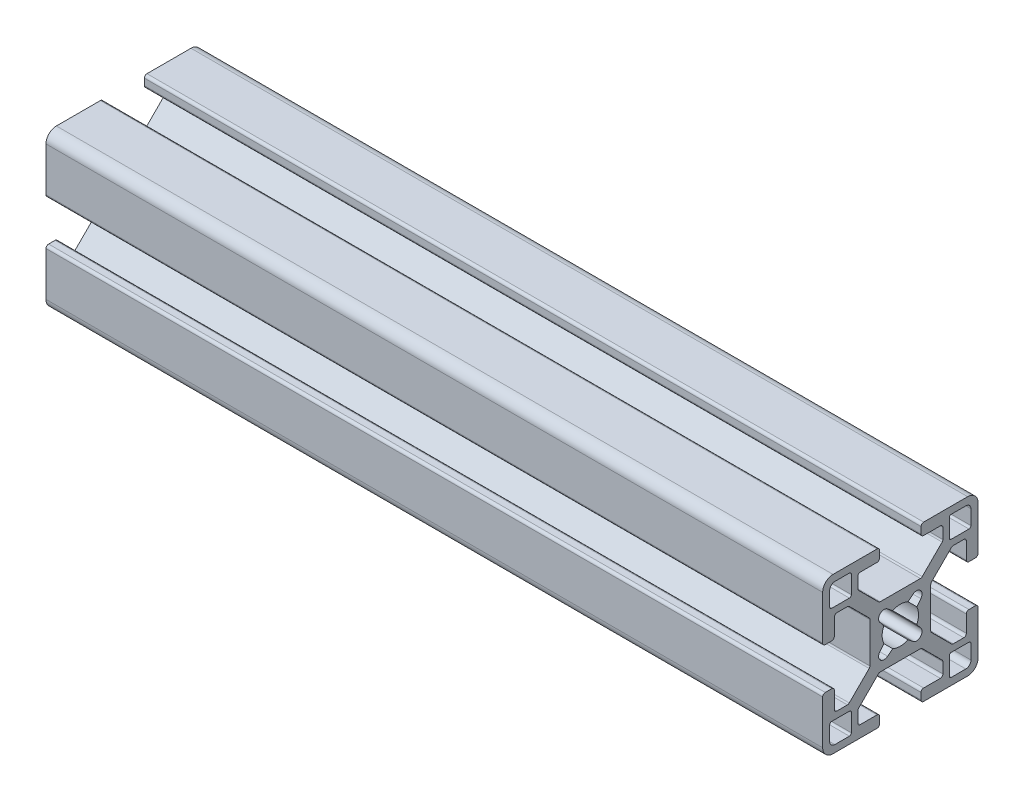
SolidWorks part; units mm, degrees
ref_plane "Front" through (0, 0, 0) normal (0, 0, 1) x (1, 0, 0)
ref_plane "Top" through (0, 0, 0) normal (0, 1, 0) x (1, 0, 0)
ref_plane "Right" through (0, 0, 0) normal (1, 0, 0) x (0, 0, -1)
sketch3d "3DSketch1"
  line L0 (0, 0, 0) -> (150, 0, 0)
  dimension "D1" = 150
other "Perfil com. aluminio PERFIL COMER. 30 X 30(1)"
ref_plane "Plano1" through (0, 0, 0) normal (1, 0, 0) x (0, 0, -1)
sketch "Esboço1" plane through (0, 0, 0) normal (1, 0, 0) x (0, 0, -1)
  line L10 (-3.1849, 1.488) -> (-3.9634, 2.4631)
  line L11 (-2.4631, 3.9634) -> (-1.488, 3.1849)
  line L16 (-9.46, 13.26) -> (-9.46, 9.84)
  line L17 (-9.84, 9.46) -> (-13.26, 9.46)
  line L18 (-13.64, 9.84) -> (-13.64, 12.64)
  line L19 (-12.64, 13.64) -> (-9.84, 13.64)
  line L44 (0, 5.8727) -> (-3.8729, 5.8727)
  line L45 (-4.2264, 6.0192) -> (-8.0736, 9.8663)
  line L46 (-8.22, 10.2198) -> (-8.22, 12.25)
  line L47 (-7.72, 12.75) -> (-4.5, 12.75)
  line L48 (-4, 13.25) -> (-4, 14.5)
  line L49 (-4.5, 15) -> (-13, 15)
  line L50 (-15, 13) -> (-15, 4.5)
  line L51 (-14.5, 4) -> (-13.25, 4)
  line L52 (-12.75, 4.5) -> (-12.75, 7.72)
  line L53 (-12.25, 8.22) -> (-10.2198, 8.22)
  line L54 (-9.8663, 8.0736) -> (-6.0192, 4.2264)
  line L55 (-5.8727, 3.8729) -> (-5.8727, 0)
  line L84 (13.64, 12.64) -> (13.64, 9.84)
  line L91 (15, 4.5) -> (15, 13)
  line L92 (13, 15) -> (4.5, 15)
  line L93 (4, 14.5) -> (4, 13.25)
  line L94 (4.5, 12.75) -> (7.72, 12.75)
  line L95 (8.22, 12.25) -> (8.22, 10.2198)
  line L96 (8.0736, 9.8663) -> (4.2264, 6.0192)
  line L97 (3.8729, 5.8727) -> (0, 5.8727)
  line L98 (1.488, 3.1849) -> (2.4631, 3.9634)
  line L99 (3.9634, 2.4631) -> (3.1849, 1.488)
  line L100 (5.8727, 0) -> (5.8727, 3.8729)
  line L101 (6.0192, 4.2264) -> (9.8663, 8.0736)
  line L102 (10.2198, 8.22) -> (12.25, 8.22)
  line L103 (12.75, 7.72) -> (12.75, 4.5)
  line L104 (13.25, 4) -> (14.5, 4)
  line L105 (13.26, 9.46) -> (9.84, 9.46)
  line L112 (9.46, 9.84) -> (9.46, 13.26)
  line L113 (9.84, 13.64) -> (12.64, 13.64)
  line L114 (12.64, -13.64) -> (9.84, -13.64)
  line L115 (4.5, -15) -> (13, -15)
  line L116 (15, -13) -> (15, -4.5)
  line L117 (14.5, -4) -> (13.25, -4)
  line L118 (12.75, -4.5) -> (12.75, -7.72)
  line L119 (12.25, -8.22) -> (10.2198, -8.22)
  line L120 (9.8663, -8.0736) -> (6.0192, -4.2264)
  line L121 (5.8727, -3.8729) -> (5.8727, 0)
  line L122 (3.1849, -1.488) -> (3.9634, -2.4631)
  line L123 (2.4631, -3.9634) -> (1.488, -3.1849)
  line L124 (0, -5.8727) -> (3.8729, -5.8727)
  line L125 (4.2264, -6.0192) -> (8.0736, -9.8663)
  line L126 (8.22, -10.2198) -> (8.22, -12.25)
  line L133 (7.72, -12.75) -> (4.5, -12.75)
  line L134 (4, -13.25) -> (4, -14.5)
  line L135 (9.46, -13.26) -> (9.46, -9.84)
  line L136 (9.84, -9.46) -> (13.26, -9.46)
  line L137 (13.64, -9.84) -> (13.64, -12.64)
  line L138 (-13.64, -12.64) -> (-13.64, -9.84)
  line L139 (-15, -4.5) -> (-15, -13)
  line L140 (-13, -15) -> (-4.5, -15)
  line L141 (-4, -14.5) -> (-4, -13.25)
  line L142 (-4.5, -12.75) -> (-7.72, -12.75)
  line L143 (-8.22, -12.25) -> (-8.22, -10.2198)
  line L144 (-8.0736, -9.8663) -> (-4.2264, -6.0192)
  line L145 (-3.8729, -5.8727) -> (0, -5.8727)
  line L146 (-1.488, -3.1849) -> (-2.4631, -3.9634)
  line L147 (-3.9634, -2.4631) -> (-3.1849, -1.488)
  line L148 (3.9634, 2.4631) -> (3.1849, 1.488) [skipped]
  line L149 (13.26, 9.46) -> (9.84, 9.46) [skipped]
  line L150 (9.46, 9.84) -> (9.46, 13.26) [skipped]
  line L151 (9.84, 13.64) -> (12.64, 13.64) [skipped]
  line L152 (13.64, 12.64) -> (13.64, 9.84) [skipped]
  line L153 (5.8727, 0) -> (5.8727, 3.8729) [skipped]
  line L154 (6.0192, 4.2264) -> (9.8663, 8.0736) [skipped]
  line L155 (10.2198, 8.22) -> (12.25, 8.22) [skipped]
  line L156 (12.75, 7.72) -> (12.75, 4.5) [skipped]
  line L157 (13.25, 4) -> (14.5, 4) [skipped]
  line L158 (15, 4.5) -> (15, 13) [skipped]
  line L159 (13, 15) -> (4.5, 15) [skipped]
  line L160 (4, 14.5) -> (4, 13.25) [skipped]
  line L161 (4.5, 12.75) -> (7.72, 12.75) [skipped]
  line L162 (8.22, 12.25) -> (8.22, 10.2198) [skipped]
  line L163 (8.0736, 9.8663) -> (4.2264, 6.0192) [skipped]
  line L164 (3.8729, 5.8727) -> (0, 5.8727) [skipped]
  line L165 (3.1849, -1.488) -> (3.9634, -2.4631) [skipped]
  line L166 (9.46, -13.26) -> (9.46, -9.84) [skipped]
  line L167 (9.84, -9.46) -> (13.26, -9.46) [skipped]
  line L168 (13.64, -9.84) -> (13.64, -12.64) [skipped]
  line L169 (12.64, -13.64) -> (9.84, -13.64) [skipped]
  line L170 (0, -5.8727) -> (3.8729, -5.8727) [skipped]
  line L171 (4.2264, -6.0192) -> (8.0736, -9.8663) [skipped]
  line L172 (8.22, -10.2198) -> (8.22, -12.25) [skipped]
  line L173 (7.72, -12.75) -> (4.5, -12.75) [skipped]
  line L174 (4, -13.25) -> (4, -14.5) [skipped]
  line L175 (4.5, -15) -> (13, -15) [skipped]
  line L176 (15, -13) -> (15, -4.5) [skipped]
  line L177 (14.5, -4) -> (13.25, -4) [skipped]
  line L178 (12.75, -4.5) -> (12.75, -7.72) [skipped]
  line L179 (12.25, -8.22) -> (10.2198, -8.22) [skipped]
  line L180 (9.8663, -8.0736) -> (6.0192, -4.2264) [skipped]
  line L181 (5.8727, -3.8729) -> (5.8727, 0) [skipped]
  line L182 (-9.46, -9.84) -> (-9.46, -13.26) [skipped]
  line L183 (-9.84, -13.64) -> (-12.64, -13.64) [skipped]
  line L184 (-13.64, -12.64) -> (-13.64, -9.84) [skipped]
  line L185 (-15, -4.5) -> (-15, -13) [skipped]
  line L186 (-13, -15) -> (-4.5, -15) [skipped]
  line L187 (-4, -14.5) -> (-4, -13.25) [skipped]
  line L188 (-4.5, -12.75) -> (-7.72, -12.75) [skipped]
  line L189 (-8.22, -12.25) -> (-8.22, -10.2198) [skipped]
  line L190 (2.4631, -3.9634) -> (1.488, -3.1849) [skipped]
  line L191 (-1.488, -3.1849) -> (-2.4631, -3.9634) [skipped]
  line L192 (-13.26, -9.46) -> (-9.84, -9.46) [skipped]
  line L193 (-6.0192, -4.2264) -> (-9.8663, -8.0736) [skipped]
  line L194 (-10.2198, -8.22) -> (-12.25, -8.22) [skipped]
  line L195 (-12.75, -7.72) -> (-12.75, -4.5) [skipped]
  line L196 (-13.25, -4) -> (-14.5, -4) [skipped]
  line L197 (-8.0736, -9.8663) -> (-4.2264, -6.0192) [skipped]
  line L198 (-3.8729, -5.8727) -> (0, -5.8727) [skipped]
  line L199 (1.488, 3.1849) -> (2.4631, 3.9634) [skipped]
  line L200 (-3.9634, -2.4631) -> (-3.1849, -1.488) [skipped]
  line L201 (-5.8727, 0) -> (-5.8727, -3.8729) [skipped]
  line L202 (-5.8727, 0) -> (-5.8727, -3.8729)
  line L203 (-6.0192, -4.2264) -> (-9.8663, -8.0736)
  line L204 (-10.2198, -8.22) -> (-12.25, -8.22)
  line L205 (-12.75, -7.72) -> (-12.75, -4.5)
  line L206 (-13.25, -4) -> (-14.5, -4)
  line L207 (-13.26, -9.46) -> (-9.84, -9.46)
  line L208 (-9.46, -9.84) -> (-9.46, -13.26)
  line L209 (-9.84, -13.64) -> (-12.64, -13.64)
  arc A10 (-3.1849, 1.488) -> (-3.5154, 0) centre (0, 0) ccw
  arc A11 (-2.4631, 3.9634) -> (-3.9634, 2.4631) centre (-3.1292, 3.1292) ccw
  arc A12 (0, 3.5154) -> (-1.488, 3.1849) centre (0, 0) ccw
  arc A16 (-9.46, 13.26) -> (-9.84, 13.64) centre (-9.84, 13.26) ccw
  arc A17 (-9.84, 9.46) -> (-9.46, 9.84) centre (-9.84, 9.84) ccw
  arc A18 (-13.64, 9.84) -> (-13.26, 9.46) centre (-13.26, 9.84) ccw
  arc A19 (-12.64, 13.64) -> (-13.64, 12.64) centre (-12.64, 12.64) ccw
  arc A41 (-7.72, 12.75) -> (-8.22, 12.25) centre (-7.72, 12.25) ccw
  arc A42 (-4.5, 12.75) -> (-4, 13.25) centre (-4.5, 13.25) ccw
  arc A43 (-4, 14.5) -> (-4.5, 15) centre (-4.5, 14.5) ccw
  arc A44 (-13, 15) -> (-15, 13) centre (-13, 13) ccw
  arc A45 (-15, 4.5) -> (-14.5, 4) centre (-14.5, 4.5) ccw
  arc A46 (-13.25, 4) -> (-12.75, 4.5) centre (-13.25, 4.5) ccw
  arc A47 (-12.25, 8.22) -> (-12.75, 7.72) centre (-12.25, 7.72) ccw
  arc A50 (-6.0192, 4.2264) -> (-5.8727, 3.8729) centre (-6.3727, 3.8729) cw
  arc A51 (-4.2264, 6.0192) -> (-3.8729, 5.8727) centre (-3.8729, 6.3727) ccw
  arc A52 (-8.22, 10.2198) -> (-8.0736, 9.8663) centre (-7.72, 10.2198) ccw
  arc A53 (-10.2198, 8.22) -> (-9.8663, 8.0736) centre (-10.2198, 7.72) cw
  arc A68 (15, 13) -> (13, 15) centre (13, 13) ccw
  arc A69 (13.64, 12.64) -> (12.64, 13.64) centre (12.64, 12.64) ccw
  arc A70 (4.5, 15) -> (4, 14.5) centre (4.5, 14.5) ccw
  arc A71 (4, 13.25) -> (4.5, 12.75) centre (4.5, 13.25) ccw
  arc A79 (8.22, 12.25) -> (7.72, 12.75) centre (7.72, 12.25) ccw
  arc A80 (8.22, 10.2198) -> (8.0736, 9.8663) centre (7.72, 10.2198) cw
  arc A81 (4.2264, 6.0192) -> (3.8729, 5.8727) centre (3.8729, 6.3727) cw
  arc A82 (1.488, 3.1849) -> (0, 3.5154) centre (0, 0) ccw
  arc A83 (3.9634, 2.4631) -> (2.4631, 3.9634) centre (3.1292, 3.1292) ccw
  arc A84 (3.5154, 0) -> (3.1849, 1.488) centre (0, 0) ccw
  arc A85 (6.0192, 4.2264) -> (5.8727, 3.8729) centre (6.3727, 3.8729) ccw
  arc A86 (10.2198, 8.22) -> (9.8663, 8.0736) centre (10.2198, 7.72) ccw
  arc A87 (12.75, 7.72) -> (12.25, 8.22) centre (12.25, 7.72) ccw
  arc A88 (12.75, 4.5) -> (13.25, 4) centre (13.25, 4.5) ccw
  arc A89 (14.5, 4) -> (15, 4.5) centre (14.5, 4.5) ccw
  arc A97 (13.26, 9.46) -> (13.64, 9.84) centre (13.26, 9.84) ccw
  arc A98 (9.46, 9.84) -> (9.84, 9.46) centre (9.84, 9.84) ccw
  arc A99 (9.84, 13.64) -> (9.46, 13.26) centre (9.84, 13.26) ccw
  arc A100 (13, -15) -> (15, -13) centre (13, -13) ccw
  arc A101 (12.64, -13.64) -> (13.64, -12.64) centre (12.64, -12.64) ccw
  arc A102 (15, -4.5) -> (14.5, -4) centre (14.5, -4.5) ccw
  arc A103 (13.25, -4) -> (12.75, -4.5) centre (13.25, -4.5) ccw
  arc A104 (12.25, -8.22) -> (12.75, -7.72) centre (12.25, -7.72) ccw
  arc A105 (10.2198, -8.22) -> (9.8663, -8.0736) centre (10.2198, -7.72) cw
  arc A106 (6.0192, -4.2264) -> (5.8727, -3.8729) centre (6.3727, -3.8729) cw
  arc A107 (3.1849, -1.488) -> (3.5154, 0) centre (0, 0) ccw
  arc A108 (3.9634, 2.4631) -> (2.4631, 3.9634) centre (3.1292, 3.1292) ccw [skipped]
  arc A109 (13.26, 9.46) -> (13.64, 9.84) centre (13.26, 9.84) ccw [skipped]
  arc A110 (9.46, 9.84) -> (9.84, 9.46) centre (9.84, 9.84) ccw [skipped]
  arc A111 (9.84, 13.64) -> (9.46, 13.26) centre (9.84, 13.26) ccw [skipped]
  arc A112 (13.64, 12.64) -> (12.64, 13.64) centre (12.64, 12.64) ccw [skipped]
  arc A113 (12.75, 7.72) -> (12.25, 8.22) centre (12.25, 7.72) ccw [skipped]
  arc A114 (12.75, 4.5) -> (13.25, 4) centre (13.25, 4.5) ccw [skipped]
  arc A115 (14.5, 4) -> (15, 4.5) centre (14.5, 4.5) ccw [skipped]
  arc A116 (15, 13) -> (13, 15) centre (13, 13) ccw [skipped]
  arc A117 (4.5, 15) -> (4, 14.5) centre (4.5, 14.5) ccw [skipped]
  arc A118 (4, 13.25) -> (4.5, 12.75) centre (4.5, 13.25) ccw [skipped]
  arc A119 (8.22, 12.25) -> (7.72, 12.75) centre (7.72, 12.25) ccw [skipped]
  arc A120 (4.2264, 6.0192) -> (3.8729, 5.8727) centre (3.8729, 6.3727) cw [skipped]
  arc A121 (6.0192, 4.2264) -> (5.8727, 3.8729) centre (6.3727, 3.8729) ccw [skipped]
  arc A122 (10.2198, 8.22) -> (9.8663, 8.0736) centre (10.2198, 7.72) ccw [skipped]
  arc A123 (8.22, 10.2198) -> (8.0736, 9.8663) centre (7.72, 10.2198) cw [skipped]
  arc A124 (2.4631, -3.9634) -> (3.9634, -2.4631) centre (3.1292, -3.1292) ccw [skipped]
  arc A125 (9.46, -13.26) -> (9.84, -13.64) centre (9.84, -13.26) ccw [skipped]
  arc A126 (9.84, -9.46) -> (9.46, -9.84) centre (9.84, -9.84) ccw [skipped]
  arc A127 (13.64, -9.84) -> (13.26, -9.46) centre (13.26, -9.84) ccw [skipped]
  arc A128 (12.64, -13.64) -> (13.64, -12.64) centre (12.64, -12.64) ccw [skipped]
  arc A129 (7.72, -12.75) -> (8.22, -12.25) centre (7.72, -12.25) ccw [skipped]
  arc A130 (4.5, -12.75) -> (4, -13.25) centre (4.5, -13.25) ccw [skipped]
  arc A131 (4, -14.5) -> (4.5, -15) centre (4.5, -14.5) ccw [skipped]
  arc A132 (13, -15) -> (15, -13) centre (13, -13) ccw [skipped]
  arc A133 (15, -4.5) -> (14.5, -4) centre (14.5, -4.5) ccw [skipped]
  arc A134 (13.25, -4) -> (12.75, -4.5) centre (13.25, -4.5) ccw [skipped]
  arc A135 (12.25, -8.22) -> (12.75, -7.72) centre (12.25, -7.72) ccw [skipped]
  arc A136 (6.0192, -4.2264) -> (5.8727, -3.8729) centre (6.3727, -3.8729) cw [skipped]
  arc A137 (4.2264, -6.0192) -> (3.8729, -5.8727) centre (3.8729, -6.3727) ccw [skipped]
  arc A138 (8.22, -10.2198) -> (8.0736, -9.8663) centre (7.72, -10.2198) ccw [skipped]
  arc A139 (10.2198, -8.22) -> (9.8663, -8.0736) centre (10.2198, -7.72) cw [skipped]
  arc A140 (-9.84, -13.64) -> (-9.46, -13.26) centre (-9.84, -13.26) ccw [skipped]
  arc A141 (-13.64, -12.64) -> (-12.64, -13.64) centre (-12.64, -12.64) ccw [skipped]
  arc A142 (-15, -13) -> (-13, -15) centre (-13, -13) ccw [skipped]
  arc A143 (-4.5, -15) -> (-4, -14.5) centre (-4.5, -14.5) ccw [skipped]
  arc A144 (-4, -13.25) -> (-4.5, -12.75) centre (-4.5, -13.25) ccw [skipped]
  arc A145 (-8.22, -12.25) -> (-7.72, -12.75) centre (-7.72, -12.25) ccw [skipped]
  arc A146 (0, -3.5154) -> (1.488, -3.1849) centre (0, 0) ccw [skipped]
  arc A147 (-1.488, -3.1849) -> (0, -3.5154) centre (0, 0) ccw [skipped]
  arc A148 (-3.9634, -2.4631) -> (-2.4631, -3.9634) centre (-3.1292, -3.1292) ccw [skipped]
  arc A149 (-13.26, -9.46) -> (-13.64, -9.84) centre (-13.26, -9.84) ccw [skipped]
  arc A150 (-9.46, -9.84) -> (-9.84, -9.46) centre (-9.84, -9.84) ccw [skipped]
  arc A151 (-12.75, -7.72) -> (-12.25, -8.22) centre (-12.25, -7.72) ccw [skipped]
  arc A152 (-12.75, -4.5) -> (-13.25, -4) centre (-13.25, -4.5) ccw [skipped]
  arc A153 (-14.5, -4) -> (-15, -4.5) centre (-14.5, -4.5) ccw [skipped]
  arc A154 (-4.2264, -6.0192) -> (-3.8729, -5.8727) centre (-3.8729, -6.3727) cw [skipped]
  arc A155 (-6.0192, -4.2264) -> (-5.8727, -3.8729) centre (-6.3727, -3.8729) ccw [skipped]
  arc A156 (-10.2198, -8.22) -> (-9.8663, -8.0736) centre (-10.2198, -7.72) ccw [skipped]
  arc A157 (-8.22, -10.2198) -> (-8.0736, -9.8663) centre (-7.72, -10.2198) cw [skipped]
  arc A158 (3.5154, 0) -> (3.1849, 1.488) centre (0, 0) ccw [skipped]
  arc A159 (3.1849, -1.488) -> (3.5154, 0) centre (0, 0) ccw [skipped]
  arc A160 (1.488, 3.1849) -> (0, 3.5154) centre (0, 0) ccw [skipped]
  arc A161 (-3.5154, 0) -> (-3.1849, -1.488) centre (0, 0) ccw [skipped]
  arc A162 (2.4631, -3.9634) -> (3.9634, -2.4631) centre (3.1292, -3.1292) ccw
  arc A163 (0, -3.5154) -> (1.488, -3.1849) centre (0, 0) ccw
  arc A164 (4.2264, -6.0192) -> (3.8729, -5.8727) centre (3.8729, -6.3727) ccw
  arc A165 (8.22, -10.2198) -> (8.0736, -9.8663) centre (7.72, -10.2198) ccw
  arc A166 (7.72, -12.75) -> (8.22, -12.25) centre (7.72, -12.25) ccw
  arc A167 (4.5, -12.75) -> (4, -13.25) centre (4.5, -13.25) ccw
  arc A168 (4, -14.5) -> (4.5, -15) centre (4.5, -14.5) ccw
  arc A169 (9.46, -13.26) -> (9.84, -13.64) centre (9.84, -13.26) ccw
  arc A170 (9.84, -9.46) -> (9.46, -9.84) centre (9.84, -9.84) ccw
  arc A171 (13.64, -9.84) -> (13.26, -9.46) centre (13.26, -9.84) ccw
  arc A172 (-15, -13) -> (-13, -15) centre (-13, -13) ccw
  arc A173 (-13.64, -12.64) -> (-12.64, -13.64) centre (-12.64, -12.64) ccw
  arc A174 (-4.5, -15) -> (-4, -14.5) centre (-4.5, -14.5) ccw
  arc A175 (-4, -13.25) -> (-4.5, -12.75) centre (-4.5, -13.25) ccw
  arc A176 (-8.22, -12.25) -> (-7.72, -12.75) centre (-7.72, -12.25) ccw
  arc A177 (-8.22, -10.2198) -> (-8.0736, -9.8663) centre (-7.72, -10.2198) cw
  arc A178 (-4.2264, -6.0192) -> (-3.8729, -5.8727) centre (-3.8729, -6.3727) cw
  arc A179 (-1.488, -3.1849) -> (0, -3.5154) centre (0, 0) ccw
  arc A180 (-3.9634, -2.4631) -> (-2.4631, -3.9634) centre (-3.1292, -3.1292) ccw
  arc A181 (-3.5154, 0) -> (-3.1849, -1.488) centre (0, 0) ccw
  arc A182 (-6.0192, -4.2264) -> (-5.8727, -3.8729) centre (-6.3727, -3.8729) ccw
  arc A183 (-10.2198, -8.22) -> (-9.8663, -8.0736) centre (-10.2198, -7.72) ccw
  arc A184 (-12.75, -7.72) -> (-12.25, -8.22) centre (-12.25, -7.72) ccw
  arc A185 (-12.75, -4.5) -> (-13.25, -4) centre (-13.25, -4.5) ccw
  arc A186 (-14.5, -4) -> (-15, -4.5) centre (-14.5, -4.5) ccw
  arc A187 (-13.26, -9.46) -> (-13.64, -9.84) centre (-13.26, -9.84) ccw
  arc A188 (-9.46, -9.84) -> (-9.84, -9.46) centre (-9.84, -9.84) ccw
  arc A189 (-9.84, -13.64) -> (-9.46, -13.26) centre (-9.84, -13.26) ccw
  point P0 (-8.75, 15)
  point P9 (0, 0)
  point P12 (-4.08, 5.8727)
  point P15 (-8.22, 10.0127)
  point P18 (-10.0127, 8.22)
  point P93 (0, 0)
  point P171 (0, 0)
  point P221 (0, 0)
  point P232 (0, 0)
  point P233 (0, 0)
  point P450 (0, 0)
  dimension "D3" = 1.0675
  dimension "D6" = 1.36
  dimension "D9" = 0.38
  dimension "D10" = 1
  dimension "D11" = 2
  dimension "D17" = 135
  dimension "D18" = 1.24
  dimension "D25" = 3.5154
  dimension "D39" = 0.5
  dimension "D20" = 15
  dimension "D26" = 0.5
  dimension "D4" = 167.212
  dimension "D5" = 25.043
  dimension "D7" = 1.36
  dimension "D8" = 4.18
  dimension "D12" = 4.18
  dimension "D13" = 1.24
  dimension "D14" = 2.25
  dimension "D15" = 11
  dimension "D16" = 11
  dimension "D19" = 15
  dimension "D21" = 4.14
  dimension "D22" = 38.606
  dimension "D23" = 25.043
  dimension "D24" = 38.606
  dimension "D27" = 5.8727
  dimension "D28" = 4
  dimension "D29" = 1.2477
  dimension "D30" = 4
  dimension "D33" = 135
  dimension "D38" = 0.5
